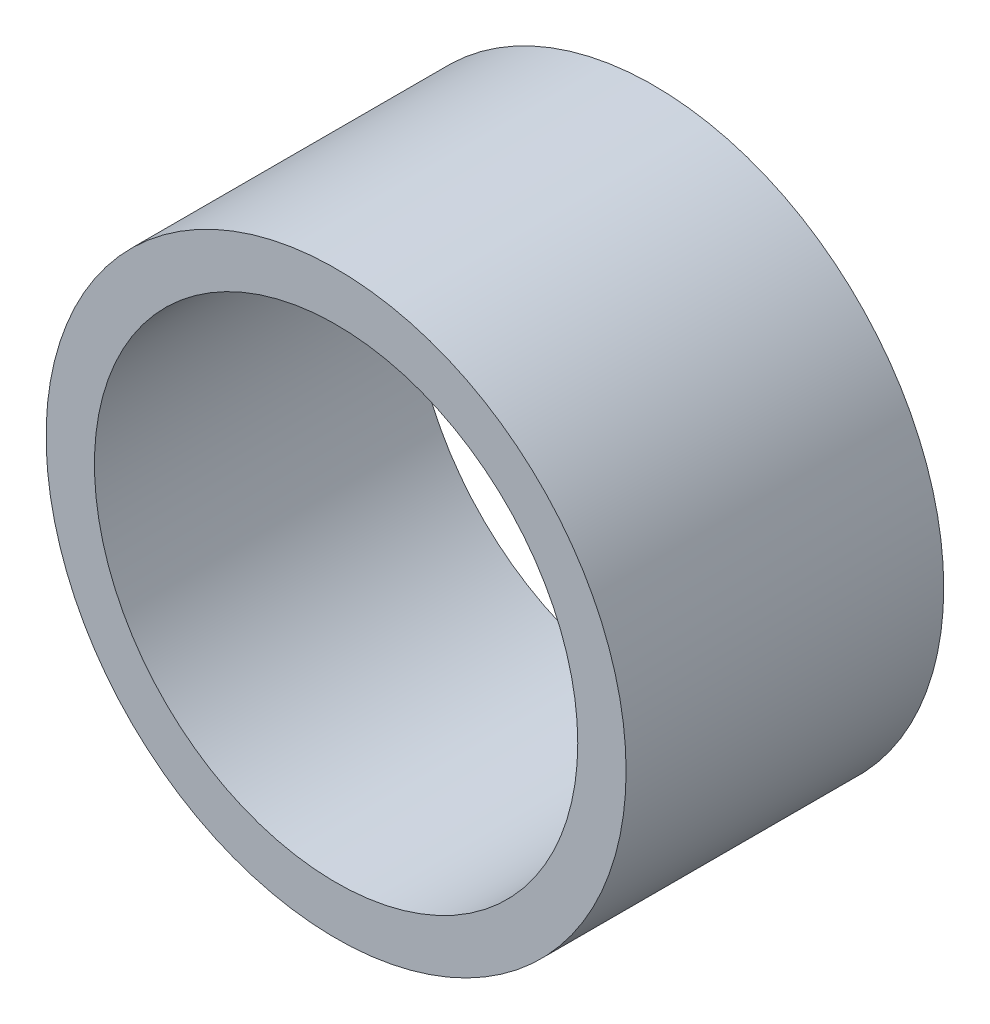
SolidWorks part; units mm, degrees
ref_plane "Front Plane" through (0, 0, 0) normal (0, 0, 1) x (1, 0, 0)
ref_plane "Top Plane" through (0, 0, 0) normal (0, 1, 0) x (1, 0, 0)
ref_plane "Right Plane" through (0, 0, 0) normal (1, 0, 0) x (0, 0, -1)
sketch "Sketch1" plane through (0, 0, 0) normal (0, 0, 1) x (1, 0, 0)
  circle A0 centre (0, 0) radius 17.5
  circle A1 centre (0, 0) radius 21
  dimension "D1" = 35
  dimension "D2" = 42
extrude "Boss-Extrude1" add sketch "Sketch1" along normal blind 23
